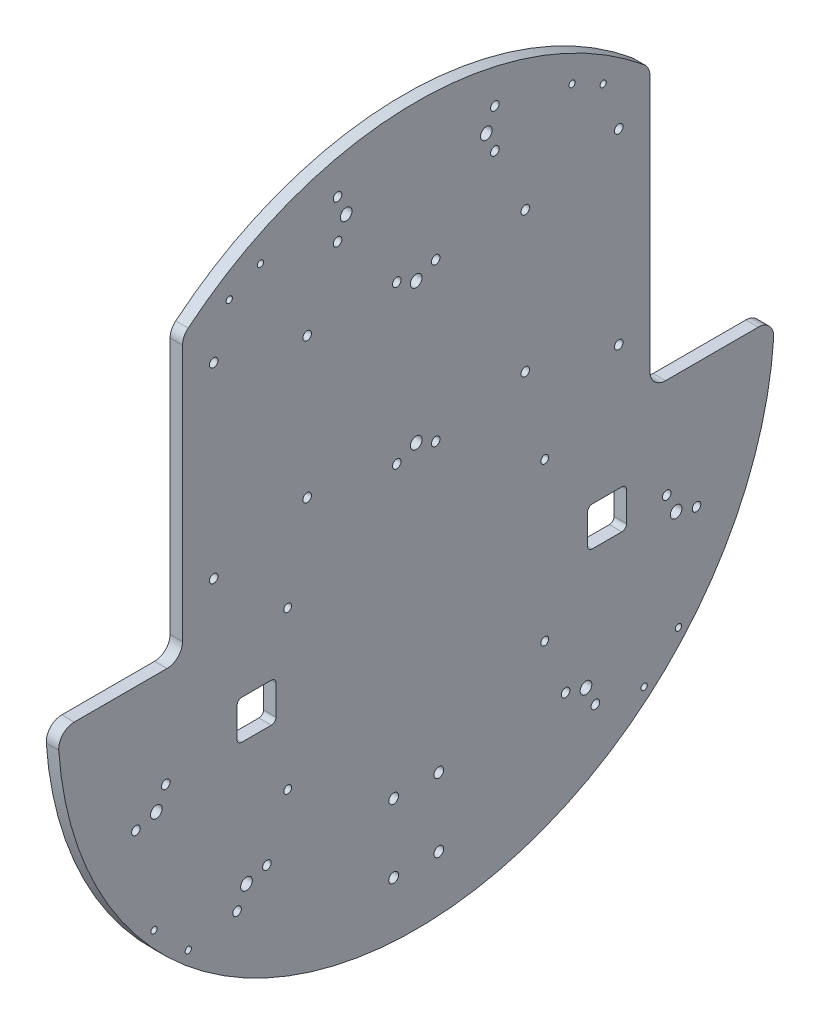
SolidWorks part; units mm, degrees
ref_plane "前视基准面" through (0, 0, 0) normal (0, 0, 1) x (1, 0, 0)
ref_plane "上视基准面" through (0, 0, 0) normal (0, 1, 0) x (1, 0, 0)
ref_plane "右视基准面" through (0, 0, 0) normal (1, 0, 0) x (0, 0, -1)
sketch "草图1" plane through (0, 0, 0) normal (1, 0, 0) x (0, 0, -1)
  circle A0 centre (0, 0) radius 230
  dimension "D1" = 460
extrude "凸台-拉伸1" add sketch "草图1" along normal blind 8
sketch "草图2" plane through (8, 0, 0) normal (1, 0, 0) x (0, 0, -1)
  line L0 (0, 0) -> (0, 50000) construction
  line L1 (-230, 195) -> (-230, -5)
  line L2 (150, 195) -> (230, 195)
  line L3 (150, 195) -> (150, -5)
  line L4 (150, -5) -> (230, -5)
  line L5 (230, 195) -> (230, -5)
  line L6 (-150, -5) -> (-230, -5)
  line L7 (-150, 195) -> (-150, -5)
  line L8 (-150, 195) -> (-230, 195)
  dimension "D1" = 200
  dimension "D2" = 80
  dimension "D3" = 150
  dimension "D4" = 5
extrude "切除-拉伸1" cut sketch "草图2" against normal blind 12
sketch "草图3" plane through (8, 0, 0) normal (1, 0, 0) x (0, 0, -1)
  line L0 (0, 0) -> (0, 50000) construction
  line L1 (-229.9456, -5) -> (-150, -5) construction
  line L2 (-130, 150) -> (-70, 150) construction
  line L3 (-130, 150) -> (-130, 30) construction
  line L4 (-130, 30) -> (-70, 30) construction
  line L5 (-70, 150) -> (-70, 30) construction
  line L6 (-150, -5) -> (-150, 174.356) construction
  line L7 (70, 150) -> (70, 30) construction
  line L8 (130, 30) -> (70, 30) construction
  line L9 (130, 150) -> (130, 30) construction
  line L10 (130, 150) -> (70, 150) construction
  circle A4 centre (-130, 150) radius 2.75
  circle A5 centre (-130, 30) radius 2.75
  circle A10 centre (130, 30) radius 2.75
  circle A11 centre (130, 150) radius 2.75
  circle A12 centre (-70, 135) radius 2.75
  circle A13 centre (-70, 45) radius 2.75
  circle A14 centre (70, 135) radius 2.75
  circle A15 centre (70, 45) radius 2.75
  dimension "D1" = 60
  dimension "D5" = 5.5
  dimension "D6" = 5.5
  dimension "D2" = 120
  dimension "D3" = 35
  dimension "D4" = 20
  dimension "D7" = 90
  dimension "D8" = 15
extrude "切除-拉伸2" cut sketch "草图3" against normal blind 12
sketch "草图4" plane through (8, 0, 0) normal (1, 0, 0) x (0, 0, -1)
  line L1 (-14.5, -150) -> (14.5, -150) construction
  line L2 (-14.5, -150) -> (-14.5, -194) construction
  line L3 (-14.5, -194) -> (14.5, -194) construction
  line L4 (14.5, -150) -> (14.5, -194) construction
  circle A0 centre (-14.5, -150) radius 3.15
  circle A1 centre (14.5, -150) radius 3.15
  circle A2 centre (14.5, -194) radius 3.15
  circle A3 centre (-14.5, -194) radius 3.15
  dimension "D5" = 6.3
  dimension "D1" = 44
  dimension "D2" = 29
  dimension "D3" = 14.5
  dimension "D4" = 150
extrude "切除-拉伸3" cut sketch "草图4" against normal blind 12
sketch "草图5" plane through (8, 0, 0) normal (1, 0, 0) x (0, 0, -1)
  line L0 (108.9626, -150.1738) -> (166.8134, -81.2298) construction
  line L1 (0, 0) -> (137.888, -115.7018) construction
  line L2 (0, 0) -> (0, 50000) construction
  line L3 (0, 0) -> (-137.888, -115.7018) construction
  line L4 (-108.9626, -150.1738) -> (-166.8134, -81.2298) construction
  line L5 (95.8517, -146.3522) -> (160.7732, -68.9817) construction
  line L6 (-50.5, 202.5) -> (50.5, 202.5) construction
  line L7 (-45, 190) -> (45, 190) construction
  circle A0 centre (166.8134, -81.2298) radius 3.75
  circle A1 centre (108.9626, -150.1738) radius 3.75
  circle A2 centre (-108.9626, -150.1738) radius 3.75
  circle A3 centre (-166.8134, -81.2298) radius 3.75
  circle A6 centre (-45, 190) radius 3.75
  circle A7 centre (45, 190) radius 3.75
  circle A8 centre (-12.5, 35) radius 2.75
  circle A9 centre (12.5, 35) radius 2.75
  circle A10 centre (95.8517, -146.3522) radius 2.75
  circle A11 centre (160.7732, -68.9817) radius 2.75
  circle A12 centre (179.9243, -85.0514) radius 2.75
  circle A13 centre (115.0028, -162.4219) radius 2.75
  circle A14 centre (-179.9243, -85.0514) radius 2.75
  circle A15 centre (-160.7732, -68.9817) radius 2.75
  circle A16 centre (-95.8517, -146.3522) radius 2.75
  circle A17 centre (-115.0028, -162.4219) radius 2.75
  circle A18 centre (50.5, 202.5) radius 2.75
  circle A19 centre (-50.5, 202.5) radius 2.75
  circle A20 centre (50.5, 177.5) radius 2.75
  circle A21 centre (-50.5, 177.5) radius 2.75
  circle A22 centre (12.5, 136) radius 2.75
  circle A23 centre (-12.5, 136) radius 2.75
  circle A24 centre (0, 130.5) radius 3.75
  circle A25 centre (0, 40.5) radius 3.75
  dimension "D5" = 7.5
  dimension "D6" = 90
  dimension "D8" = 7.5
  dimension "D10" = 5.5
  dimension "D11" = 25
  dimension "D14" = 12.5
  dimension "D17" = 5.5
  dimension "D18" = 5.5
  dimension "D22" = 5.5
  dimension "D23" = 5.5
  dimension "D24" = 5.5
  dimension "D28" = 7.5
  dimension "D29" = 7.5
  dimension "D1" = 50
  dimension "D2" = 45
  dimension "D3" = 45
  dimension "D4" = 180
  dimension "D7" = 45
  dimension "D9" = 190
  dimension "D12" = 12.5
  dimension "D13" = 35
  dimension "D15" = 101
  dimension "D16" = 50.5
  dimension "D19" = 101
  dimension "D20" = 50.5
  dimension "D21" = 12.5
  dimension "D25" = 12.5
  dimension "D26" = 12.5
  dimension "D27" = 101
  dimension "D30" = 90
  dimension "D31" = 5.5
extrude "切除-拉伸4" cut sketch "草图5" against normal blind 10
fillet "圆角1" radius 10 6 edges at (4, 174.356, 150) (4, -5, 150) (4, -5, 229.9456) (4, 174.356, -150) (4, -5, -229.9456) (4, -5, -150)
sketch "草图6" plane through (8, 0, 0) normal (1, 0, 0) x (0, 0, -1)
  line L5 (-115, -45) -> (-90, -45)
  line L6 (-115, -45) -> (-115, -70)
  line L7 (-115, -70) -> (-90, -70)
  line L8 (-90, -45) -> (-90, -70)
  dimension "D1" = 25
  dimension "D2" = 25
  dimension "D3" = 90
  dimension "D4" = 45
extrude "切除-拉伸5" cut sketch "草图6" against normal blind 10
sketch "草图7" plane through (8, 0, 0) normal (1, 0, 0) x (0, 0, -1)
  line L1 (-82.5, -10) -> (82.5, -10) construction
  line L2 (-82.5, -10) -> (-82.5, -111) construction
  line L3 (-82.5, -111) -> (82.5, -111) construction
  line L4 (82.5, -10) -> (82.5, -111) construction
  circle A2 centre (82.5, -10) radius 2.5
  circle A3 centre (82.5, -111) radius 2.5
  circle A4 centre (-82.5, -10) radius 2.5
  circle A5 centre (-82.5, -111) radius 2.5
  dimension "D5" = 5
  dimension "D6" = 5
  dimension "D7" = 5
  dimension "D8" = 5
  dimension "D1" = 165
  dimension "D2" = 101
  dimension "D3" = 82.5
  dimension "D4" = 10
extrude "切除-拉伸6" cut sketch "草图7" against normal blind 10
sketch "草图8" plane through (8, 0, 0) normal (1, 0, 0) x (0, 0, -1)
  line L1 (110, -50) -> (135, -50)
  line L2 (110, -50) -> (110, -75)
  line L3 (110, -75) -> (135, -75)
  line L4 (135, -50) -> (135, -75)
  dimension "D1" = 25
  dimension "D2" = 25
  dimension "D3" = 50
  dimension "D4" = 110
extrude "切除-拉伸7" cut sketch "草图8" against normal blind 10
fillet "圆角3" radius 3 4 edges at (4, -75, -135) (4, -75, -110) (4, -50, -110) (4, -50, -135)
sketch "草图10" plane through (8, 0, 0) normal (1, 0, 0) x (0, 0, -1)
  line L0 (0, 0) -> (35355.3391, -35355.3391) construction
  line L1 (0, 0) -> (0, 50000) construction
  line L2 (146.3012, -168.3002) -> (0, 0) construction
  line L3 (0, 0) -> (168.3002, -146.3012) construction
  line L4 (0, 0) -> (-168.3002, -146.3012) construction
  line L5 (-146.3012, -168.3002) -> (0, 0) construction
  line L6 (0, 0) -> (-35355.3391, -35355.3391) construction
  circle A0 centre (168.3002, -146.3012) radius 2
  circle A1 centre (146.3012, -168.3002) radius 2
  circle A2 centre (-146.3012, -168.3002) radius 2
  circle A3 centre (-168.3002, -146.3012) radius 2
  dimension "D2" = 4
  dimension "D6" = 4
  dimension "D1" = 45
  dimension "D3" = 4
  dimension "D4" = 223
  dimension "D5" = 223
extrude "切除-拉伸9" cut sketch "草图10" against normal through all
sketch "草图11" plane through (8, 0, 0) normal (1, 0, 0) x (0, 0, -1)
  line L0 (0, 0) -> (0, 50000) construction
  circle A0 centre (100, 190) radius 2
  circle A1 centre (120, 180) radius 2
  circle A2 centre (-120, 180) radius 2
  circle A3 centre (-100, 190) radius 2
  dimension "D1" = 190
  dimension "D3" = 4
  dimension "D4" = 10
  dimension "D6" = 4
  dimension "D2" = 100
  dimension "D5" = 20
extrude "切除-拉伸10" cut sketch "草图11" against normal blind 25
fillet "圆角4" radius 3 4 edges at (4, -70, 90) (4, -70, 115) (4, -45, 115) (4, -45, 90)
